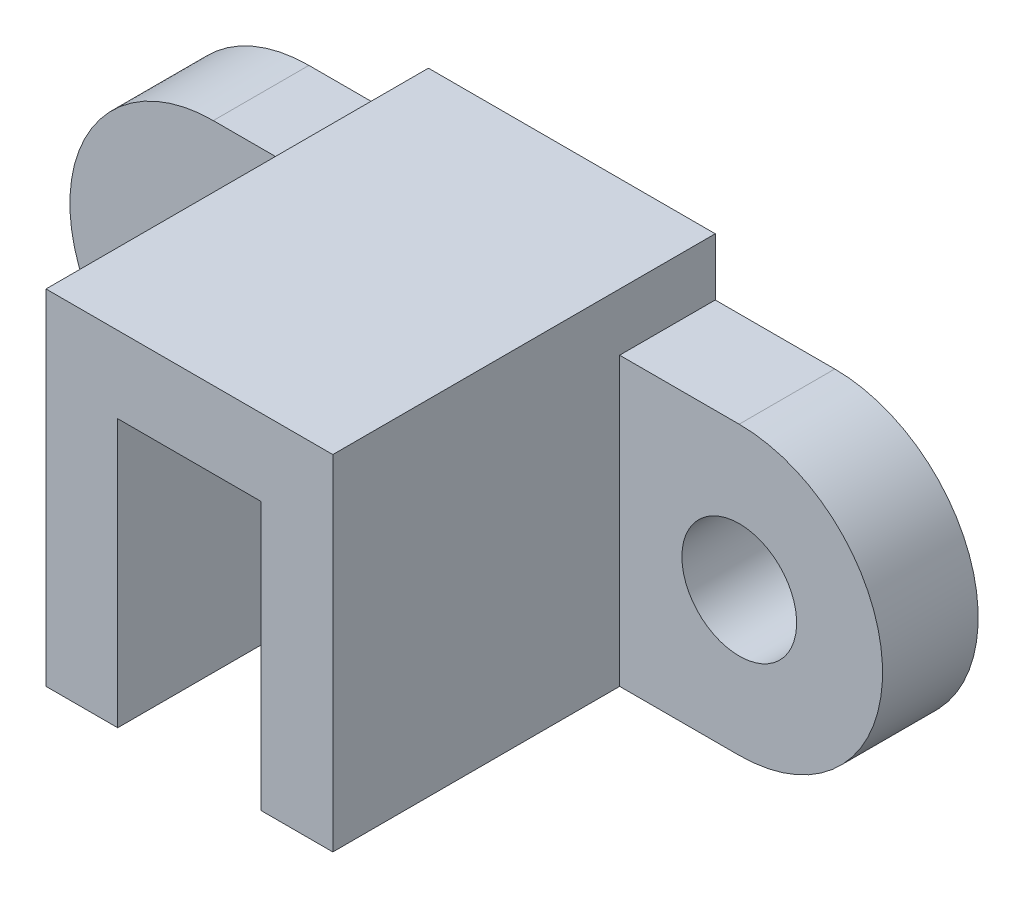
SolidWorks part; units mm, degrees
ref_plane "前视基准面" through (0, 0, 0) normal (0, 0, 1) x (1, 0, 0)
ref_plane "上视基准面" through (0, 0, 0) normal (0, 1, 0) x (1, 0, 0)
ref_plane "右视基准面" through (0, 0, 0) normal (1, 0, 0) x (0, 0, -1)
other "Configuration Table"
sketch "草图1" plane through (0, 0, 0) normal (0, 0, 1) x (1, 0, 0)
  line L1 (15, -18) -> (-15, -18)
  line L2 (15, 12) -> (15, 18)
  line L3 (15, 18) -> (-15, 18)
  line L4 (-15, 12) -> (-15, 18)
  line L5 (15, -18) -> (-15, 18) construction
  line L6 (15, 18) -> (-15, -18) construction
  line L8 (-15, 12) -> (-27.5, 12)
  line L10 (-27.5, -18) -> (-15, -18)
  line L11 (0, 0) -> (0, -23.3814) construction
  line L12 (27.5, -18) -> (15, -18)
  line L13 (15, 12) -> (27.5, 12)
  arc A0 (-27.5, 12) -> (-42.5, -3) centre (-27.5, -3) ccw
  arc A1 (-42.5, -3) -> (-27.5, -18) centre (-27.5, -3) ccw
  circle A2 centre (-27.5, -3) radius 6
  circle A3 centre (27.5, -3) radius 6
  arc A4 (42.5, -3) -> (27.5, -18) centre (27.5, -3) cw
  arc A5 (27.5, 12) -> (42.5, -3) centre (27.5, -3) cw
  point P0 (0, 0)
  point P11 (-42.5, 12)
  dimension "D5" = 15
  dimension "D1" = 30
  dimension "D3" = 27.5
extrude "凸台-拉伸1" add sketch "草图1" along normal blind 10 contours L8 A0 A1 L10 L1 L12 A4 A5 L13 L2 L3 L4
sketch "草图3" plane through (0, 0, 10) normal (0, 0, 1) x (1, 0, 0)
  line L0 (-15, 18) -> (15, 18)
  line L1 (15, 18) -> (15, -18)
  line L2 (27.5, -18) -> (-27.5, -18) construction
  line L3 (15, -18) -> (-15, -18)
  line L4 (-15, -18) -> (-15, 18)
extrude "凸台-拉伸2" add sketch "草图3" along normal blind 30
sketch "草图4" plane through (0, 0, 0) normal (0, 0, 1) x (1, 0, 0)
  circle A0 centre (-27.5, -3) radius 6
  circle A1 centre (27.511, -3) radius 6
extrude "切除-拉伸1" cut sketch "草图4" along normal blind 52
sketch "草图5" plane through (-15, 0, 0) normal (-1, 0, 0) x (0, 0, 1)
  line L1 (40, 18) -> (40, -18) construction
  line L2 (40, 10) -> (0, -12)
  line L3 (0, 12) -> (0, -18) construction
  line L4 (0, -12) -> (0, -18)
  line L5 (0, -18) -> (40, -18)
  line L6 (40, -18) -> (40, 10)
  dimension "D2" = 6
sketch "草图6" plane through (-15, 0, 0) normal (-1, 0, 0) x (0, 0, 1)
extrude "切除-拉伸2" cut sketch "草图5" against normal blind 15 from offset 7.5
